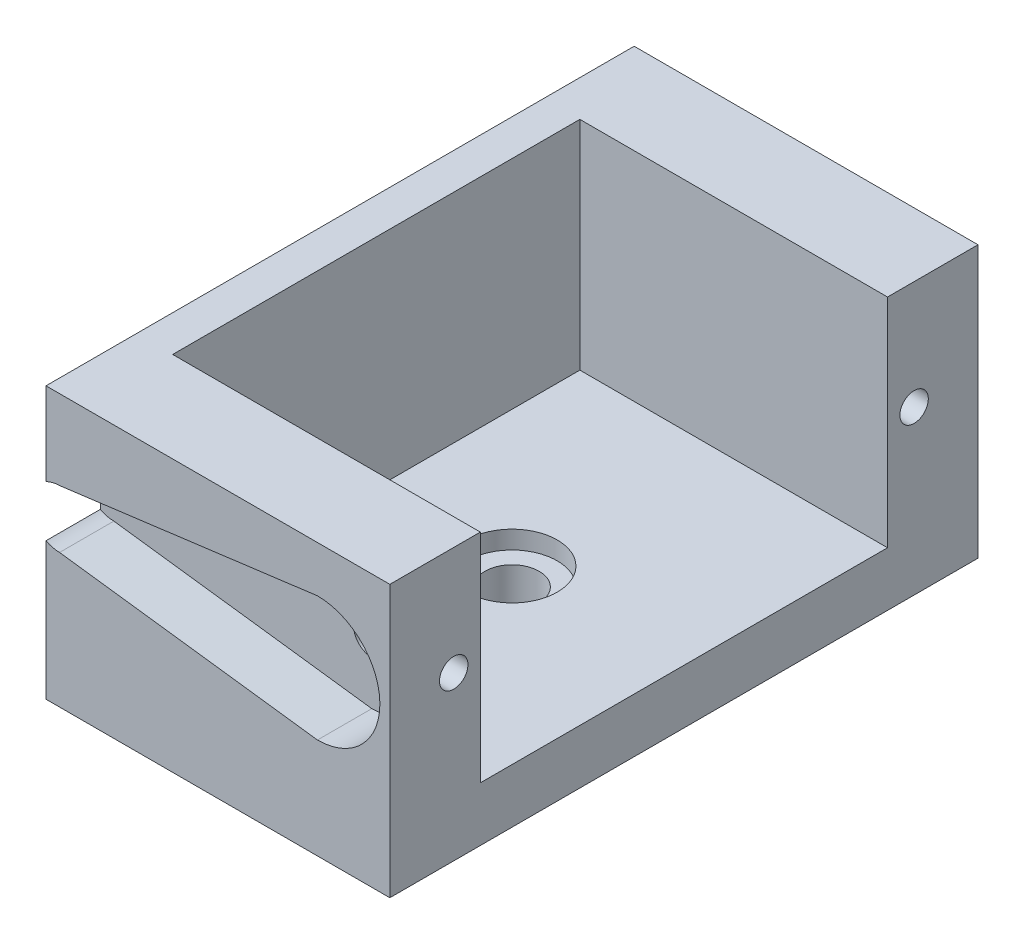
SolidWorks part; units mm, degrees
ref_plane "前视基准面" through (0, 0, 0) normal (0, 0, 1) x (1, 0, 0)
ref_plane "上视基准面" through (0, 0, 0) normal (0, 1, 0) x (1, 0, 0)
ref_plane "右视基准面" through (0, 0, 0) normal (1, 0, 0) x (0, 0, -1)
other "Configuration Table"
sketch "草图1" plane through (0, 0, 0) normal (1, 0, 0) x (0, 0, -1)
  line L1 (-11.25, -6) -> (11.25, -6)
  line L2 (-11.25, -6) -> (-11.25, 6)
  line L3 (-11.25, 6) -> (11.25, 6)
  line L4 (11.25, -6) -> (11.25, 6)
  line L5 (-11.25, -6) -> (11.25, 6) construction
  line L6 (-11.25, 6) -> (11.25, -6) construction
  line L7 (-16.25, -6) -> (16.25, -6)
  line L8 (-16.25, -6) -> (-16.25, 6)
  line L9 (-16.25, 6) -> (16.25, 6)
  line L10 (16.25, -6) -> (16.25, 6)
  line L11 (-16.25, -6) -> (16.25, 6) construction
  line L12 (-16.25, 6) -> (16.25, -6) construction
  point P0 (0, 0)
  point P6 (0, 0)
  dimension "D1" = 12
  dimension "D2" = 22.5
  dimension "D3" = 32.5
extrude "凸台-拉伸1" add sketch "草图1" along normal blind 19 contours L9 L8 L7 L2 | L7 L10 L9 L4
sketch "草图2" plane through (0, 0, 0) normal (-1, 0, 0) x (0, 0, 1)
  line L1 (-16.25, 6) -> (16.25, 6)
  line L2 (-16.25, 6) -> (-16.25, -6)
  line L3 (-16.25, -6) -> (16.25, -6)
  line L4 (16.25, 6) -> (16.25, -6)
extrude "凸台-拉伸2" add sketch "草图2" against normal blind 2
sketch "草图3" plane through (19, 0, 0) normal (1, 0, 0) x (0, 0, -1)
  line L0 (-11.25, 0) -> (-12.72, 0)
  line L1 (-11.25, -6) -> (-11.25, 6) construction
  line L2 (11.25, 0) -> (12.72, 0)
  line L3 (11.25, -6) -> (11.25, 6) construction
  circle A0 centre (-12.72, 0) radius 0.785
  circle A1 centre (12.72, 0) radius 0.785
  dimension "D3" = 1.57
  dimension "D4" = 1.57
  dimension "D1" = 1.47
  dimension "D2" = 1.47
extrude "切除-拉伸2" cut sketch "草图3" against normal blind 3
sketch "草图4" plane through (0, 0, 16.25) normal (0, 0, 1) x (1, 0, 0)
  line L0 (0, 0) -> (15, 0)
  line L1 (15, 0) -> (0.75, 0)
  line L2 (0.75, 1.6) -> (15, 3.45)
  line L3 (0.75, -1.6) -> (15, -3.45)
  circle A0 centre (15, 0) radius 3.45
  circle A1 centre (0.75, 0) radius 1.6
  dimension "D2" = 6.9
  dimension "D3" = 3.2
  dimension "D1" = 15
  dimension "D4" = 14.25
extrude "切除-拉伸3" cut sketch "草图4" against normal blind 3
sketch "草图6" plane through (19, 0, 0) normal (1, 0, 0) x (0, 0, -1)
  circle A0 centre (-12.72, 0) radius 0.785
sketch "草图7" plane through (16, 0, 0) normal (1, 0, 0) x (0, 0, -1)
  circle A0 centre (-12.72, 0) radius 0.785
extrude "凸台-拉伸3" add sketch "草图7" along normal blind 1
sketch "草图8" plane through (0, 0, 13.25) normal (0, 0, 1) x (1, 0, 0)
  line L1 (12.7458, -1.2807) -> (17.2542, -1.2807)
  line L2 (12.7458, -1.2807) -> (12.7458, 1.2807)
  line L3 (12.7458, 1.2807) -> (17.2542, 1.2807)
  line L4 (17.2542, -1.2807) -> (17.2542, 1.2807)
  line L5 (12.7458, -1.2807) -> (17.2542, 1.2807) construction
  line L6 (12.7458, 1.2807) -> (17.2542, -1.2807) construction
  circle A0 centre (15, 0) radius 1
  dimension "D1" = 2
extrude "切除-拉伸9" cut sketch "草图8" along normal blind 1
sketch "草图9" plane through (0, 0, 13.25) normal (0, 0, 1) x (1, 0, 0)
  circle A0 centre (15, 0) radius 1
  dimension "D1" = 2
extrude "切除-拉伸10" cut sketch "草图9" against normal blind 3
sketch "草图11" plane through (0, 0, -16.25) normal (0, 0, -1) x (-1, 0, 0)
  circle A0 centre (-15, 0) radius 1
  circle A1 centre (-15, 0) radius 1.5
  dimension "D1" = 3
sketch "草图12" plane through (0, 0, 11.25) normal (0, 0, -1) x (-1, 0, 0)
  circle A0 centre (-15, 0) radius 1.5
extrude "切除-拉伸11" cut sketch "草图12" against normal blind 0.5
sketch "草图13" plane through (0, -6, 0) normal (0, -1, 0) x (1, 0, 0)
  line L1 (0, 16.25) -> (19, 16.25)
  line L2 (0, 16.25) -> (0, -16.25)
  line L3 (0, -16.25) -> (19, -16.25)
  line L4 (19, 16.25) -> (19, -16.25)
extrude "凸台-拉伸4" add sketch "草图13" along normal blind 3
sketch "草图14" plane through (0, -9, 0) normal (0, -1, 0) x (1, 0, 0)
  line L0 (9.5, -983.75) -> (9.5, 49016.25) construction
  line L1 (19, 16.25) -> (0, 16.25) construction
  circle A0 centre (9.5, 0) radius 1.5
  point P5 (9.5, 16.25)
  dimension "D1" = 3
extrude "切除-拉伸12" cut sketch "草图14" against normal blind 3
sketch "草图15" plane through (0, -6, 0) normal (0, 1, 0) x (1, 0, 0)
  circle A0 centre (9.5, 0) radius 2.5
  dimension "D1" = 5
extrude "切除-拉伸13" cut sketch "草图15" against normal blind 1
